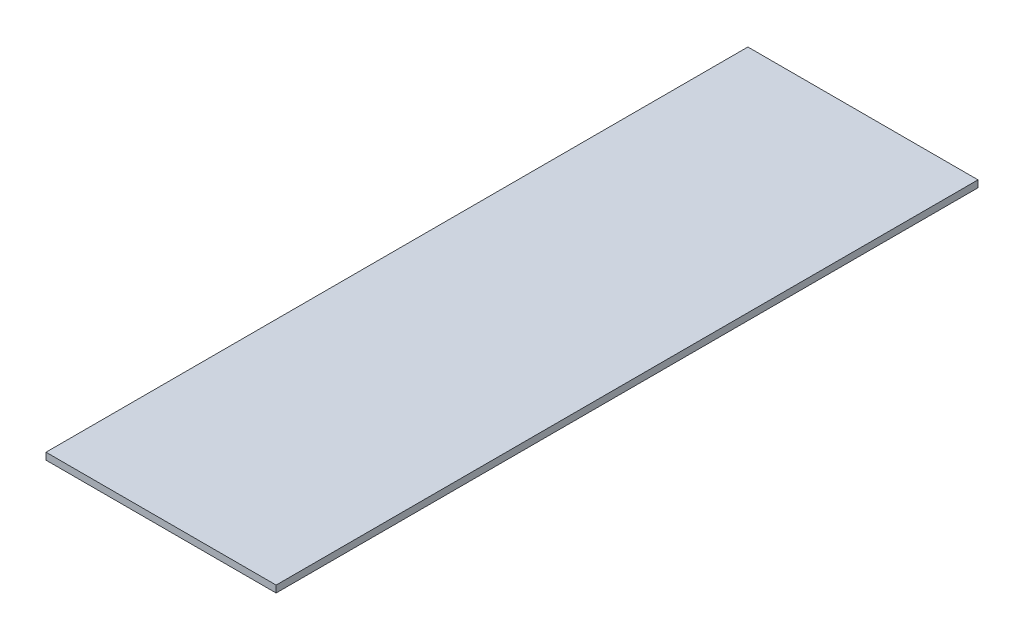
SolidWorks part; units mm, degrees
ref_plane "Alzado" through (0, 0, 0) normal (0, 0, 1) x (1, 0, 0)
ref_plane "Planta" through (0, 0, 0) normal (0, 1, 0) x (1, 0, 0)
ref_plane "Vista lateral" through (0, 0, 0) normal (1, 0, 0) x (0, 0, -1)
sketch "Croquis1" plane through (0, 0, 0) normal (0, 1, 0) x (1, 0, 0)
  line L1 (-50, 155) -> (50, 155)
  line L2 (-50, 155) -> (-50, -155)
  line L3 (-50, -155) -> (50, -155)
  line L4 (50, 155) -> (50, -155)
  line L5 (-50, 155) -> (50, -155) construction
  line L6 (-50, -155) -> (50, 155) construction
  point P0 (0, 0)
  dimension "D1" = 100
  dimension "D2" = 310
extrude "Saliente-Extruir1" add sketch "Croquis1" along normal blind 3
sketch "Croquis2" plane through (0, 3, 0) normal (0, 1, 0) x (1, 0, 0)
  line L0 (50, -155) -> (50, 155) construction
  line L1 (-50, 155) -> (50, 155)
  line L2 (-50, 155) -> (-50, 152.5)
  line L3 (-50, 152.5) -> (50, 152.5)
  line L4 (50, 155) -> (50, 152.5)
  line L5 (-50, 155) -> (50, 152.5) construction
  line L6 (-50, 152.5) -> (50, 155) construction
  line L8 (-50, -155) -> (50, -155)
  line L9 (-50, -155) -> (-50, -152.5)
  line L10 (-50, -152.5) -> (50, -152.5)
  line L11 (50, -155) -> (50, -152.5)
  line L12 (-50, -155) -> (50, -152.5) construction
  line L13 (-50, -152.5) -> (50, -155) construction
  point P4 (0, 153.75)
  point P12 (0, -153.75)
  dimension "D1" = 2.5
extrude "Cortar-Extruir1" cut sketch "Croquis2" against normal blind 10
equation "\"venesta\"= 4'grosor de la venesta"
equation "\"policarbonato\"= 4'grosor del policarbonato"
equation "\"carton_trupan\"= 3'grosor del carton trupan caso laser"
equation "\"ancho_tot\"= 310'ancho tot sin llantas"
equation "\"largo_tot\"= 400'largo tot sin camera"
equation "\"alto_estimado\"= 300'alto estimado sin lidar"
equation "\"altoparaqpaselabotella\"= 75'alto estimado para que encaje la botella"
equation "\"alturaruedaloca\"= 22"
equation "\"anchoruedaloca\"= 35"
equation "\"anchopiso1motorybaterias\"= 150"
equation "\"dist-pisorampa\"= 5"
equation "\"anchoultimopiso\"= 170"
equation "\"paredtrasera\"= 100"
equation "\"agarradorcanasta\"= 275'recolector"
equation "\"alturapiso1y2\"= 80"
equation "\"alturapiso2y3\"= 80"
equation "\"GROSOR_PARED_IMPRESION\"= 2.5"
equation "\"TOLERANCIA\"= 0.05"
equation "\"apertura\"= 70"
equation "\"D2@Croquis1\"=\"ancho_tot\""
equation "\"D1@Saliente-Extruir1\"=\"carton_trupan\""
equation "\"D1@Croquis2\"=\"GROSOR_PARED_IMPRESION\""
